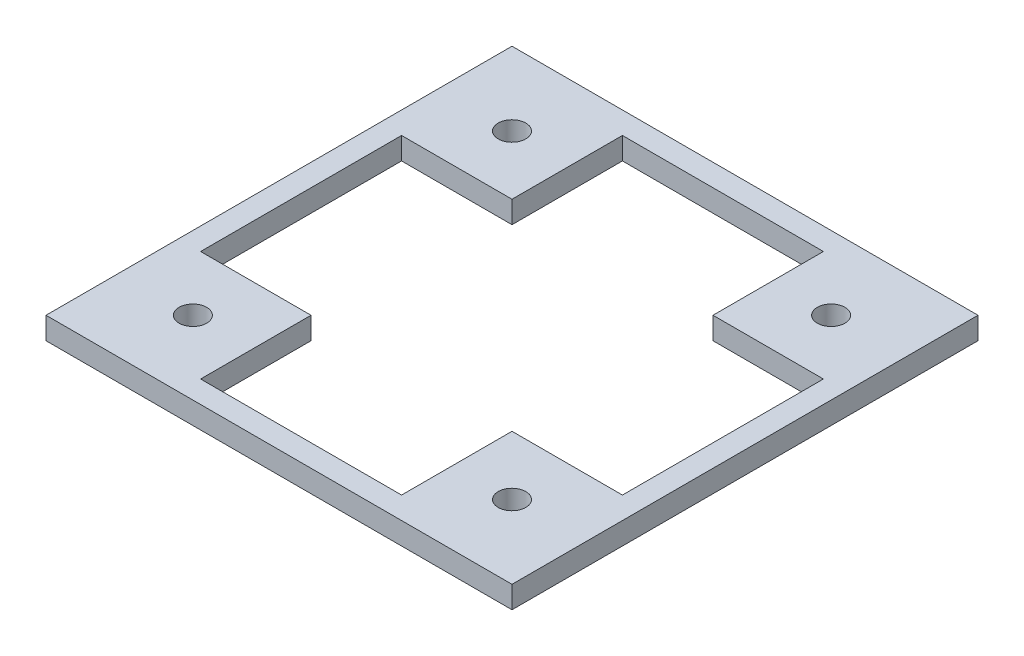
SolidWorks part; units mm, degrees
ref_plane "Front Plane" through (0, 0, 0) normal (0, 0, 1) x (1, 0, 0)
ref_plane "Top Plane" through (0, 0, 0) normal (0, 1, 0) x (1, 0, 0)
ref_plane "Right Plane" through (0, 0, 0) normal (1, 0, 0) x (0, 0, -1)
sketch "Sketch1" plane through (0, 0, 0) normal (0, 1, 0) x (1, 0, 0)
  line L0 (-82.1256, 33.9109) -> (-43.9256, 33.9109)
  line L1 (-82.1256, 53.0109) -> (-43.9256, 53.0109)
  line L2 (-82.1256, 53.0109) -> (-82.1256, 14.8109)
  line L3 (-82.1256, 14.8109) -> (-43.9256, 14.8109)
  line L4 (-43.9256, 53.0109) -> (-43.9256, 14.8109)
  line L5 (-72.1256, 53.0109) -> (-72.1256, 14.8109)
  line L6 (-84.1256, 55.0109) -> (-41.9256, 55.0109)
  line L7 (-84.1256, 55.0109) -> (-84.1256, 12.8109)
  line L8 (-84.1256, 12.8109) -> (-41.9256, 12.8109)
  line L9 (-41.9256, 55.0109) -> (-41.9256, 12.8109)
  line L10 (-84.1256, 55.0109) -> (-41.9256, 12.8109) construction
  line L11 (-84.1256, 12.8109) -> (-41.9256, 55.0109) construction
  line L12 (-53.9256, 53.0109) -> (-53.9256, 14.8109)
  line L13 (-82.1256, 24.8109) -> (-43.9256, 24.8109)
  line L14 (-82.1256, 43.0109) -> (-43.9256, 43.0109)
  point P6 (-63.0256, 33.9109)
  dimension "D1" = 38.2
  dimension "D2" = 38.2
  dimension "D3" = 42.2
  dimension "D4" = 42.2
  dimension "D5" = 10
  dimension "D6" = 10
  dimension "D7" = 10
  dimension "D8" = 10
extrude "Boss-Extrude1" add sketch "Sketch1" along normal blind 2 contours L9 L6 L7 L8 L1 L4 L3 L2 | L2 L14 L5 L1 | L12 L14 L4 L1 | L13 L12 L3 L4 | L13 L2 L3 L5
hole_wizard "M3x0.5 Tapped Hole2" positions "Sketch2" profile "Sketch3" tap size "M3x0.5" standard "ANSI Metric" end condition through all
sketch "Sketch2" plane through (0, 2, 0) normal (0, 1, 0) x (1, 0, 0)
  line L0 (-43.9256, 43.0109) -> (-43.9256, 24.8109) construction
  line L2 (-72.1256, 53.0109) -> (-53.9256, 53.0109) construction
  line L4 (-72.1256, 14.8109) -> (-53.9256, 14.8109) construction
  line L5 (-82.1256, 43.0109) -> (-82.1256, 24.8109) construction
  point P0 (-77.4756, 48.3609)
  point P2 (-48.5756, 48.3609)
  point P4 (-48.5756, 19.4609)
  point P6 (-77.4756, 19.4609)
  point P15 (-51.6256, 48.4517)
  point P18 (0, 0)
  point P25 (-36.0845, 14.4431)
  point P28 (0, 0)
  dimension "D1" = 4.65
  dimension "D2" = 4.65
  dimension "D3" = 4.65
  dimension "D4" = 4.65
  dimension "D5" = 4.65
  dimension "D6" = 4.65
  dimension "D7" = 4.65
  dimension "D8" = 4.65
sketch "Sketch3" plane through (-77.4756, 2, -48.3609) normal (1, 0, 0) x (0, 0, 1)
  line L0 (0, 0) -> (0, 2)
  line L1 (0, 2) -> (1.25, 2)
  line L2 (1.25, 2) -> (1.25, 0)
  line L5 (1.25, 0) -> (0, 0)
  line L11 (0, -6.35) -> (0, 107.95) construction
  dimension "Thread Major Dia." = 2.5
  dimension "Thru Tap Drill Depth" = 2
equation "\"module side length\"= 38"
equation "\"tolerance\"= 0.1"
equation "\"D1@Sketch1\"=\"module side length\"+\"tolerance\"*2"
equation "\"D2@Sketch1\"=\"D1@Sketch1\""
equation "\"frame thickness\"= 2"
equation "\"D3@Sketch1\"=\"D1@Sketch1\"+\"frame thickness\"*2"
equation "\"D4@Sketch1\"=\"frame thickness\"*2+\"D2@Sketch1\""
equation "\"hole panel length\"=10"
equation "\"D5@Sketch1\"=\"hole panel length\""
equation "\"D6@Sketch1\"=\"D5@Sketch1\""
equation "\"D7@Sketch1\"=\"D6@Sketch1\""
equation "\"D8@Sketch1\"=\"D5@Sketch1\""
equation "\"hole center offset\"= 4.65"
equation "\"frame depth\"=2"
equation "\"D1@Boss-Extrude1\"=\"frame depth\""
equation "\"D1@Sketch2\"=\"hole center offset\""
equation "\"D2@Sketch2\"=\"hole center offset\""
equation "\"D3@Sketch2\"=\"hole center offset\""
equation "\"D4@Sketch2\"=\"hole center offset\""
equation "\"D5@Sketch2\"=\"hole center offset\""
equation "\"D6@Sketch2\"=\"hole center offset\""
equation "\"D7@Sketch2\"=\"hole center offset\""
equation "\"D8@Sketch2\"=\"hole center offset\""
